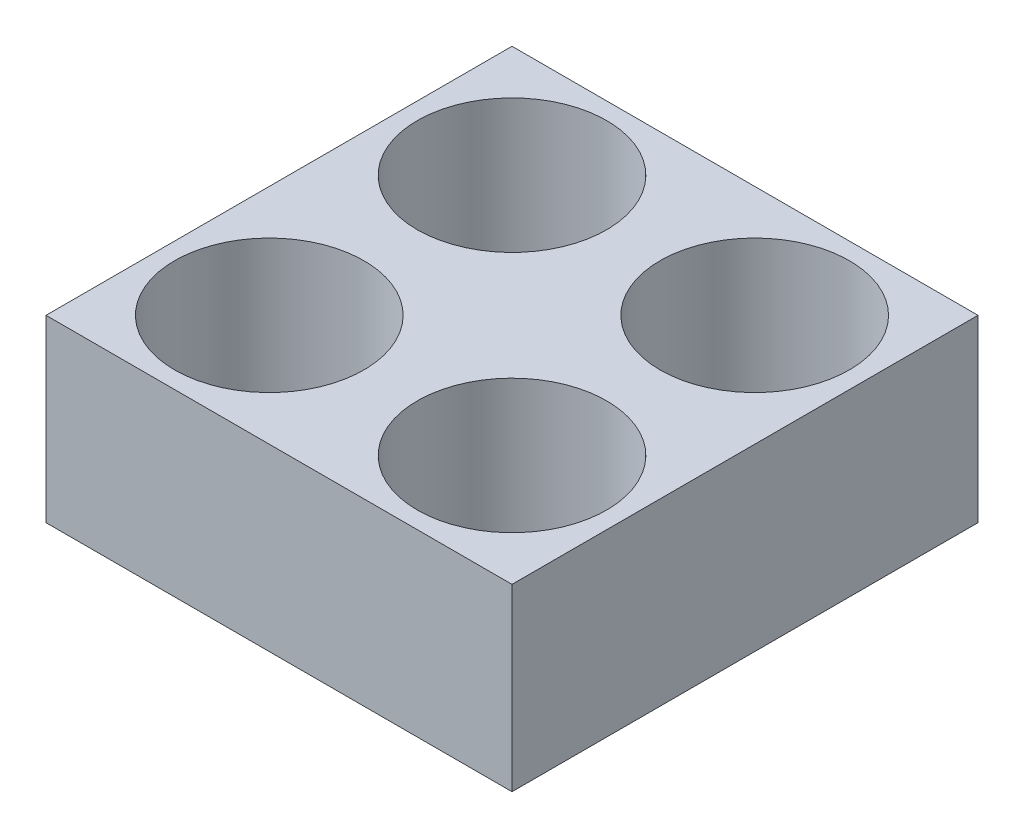
SolidWorks part; units mm, degrees
ref_plane "Front Plane" through (0, 0, 0) normal (0, 0, 1) x (1, 0, 0)
ref_plane "Top Plane" through (0, 0, 0) normal (0, 1, 0) x (1, 0, 0)
ref_plane "Right Plane" through (0, 0, 0) normal (1, 0, 0) x (0, 0, -1)
sketch "Sketch1" plane through (0, 0, 0) normal (0, 1, 0) x (1, 0, 0)
  line L0 (0, 50) -> (0, 0) construction
  line L1 (0, 0) -> (50, 0) construction
  line L2 (50, 0) -> (50, 50) construction
  line L3 (50, 50) -> (0, 50) construction
  line L4 (0, 25) -> (50, 25) construction
  line L5 (25, 50) -> (25, 0) construction
  line L7 (-23, -23) -> (73, -23)
  line L8 (-23, -23) -> (-23, 73)
  line L9 (-23, 73) -> (73, 73)
  line L10 (73, -23) -> (73, 73)
  line L11 (-23, -23) -> (73, 73) construction
  line L12 (-23, 73) -> (73, -23) construction
  circle A0 centre (0, 0) radius 19.5
  circle A1 centre (50, 0) radius 19.5
  circle A2 centre (50, 50) radius 19.5
  circle A3 centre (0, 50) radius 19.5
  point P13 (25, 25)
  dimension "D1" = 39
  dimension "D4" = 96
  dimension "D5" = 96
  dimension "D2" = 2
  dimension "D3" = 2
extrude "Boss-Extrude1" add sketch "Sketch1" along normal blind 35
sketch "Sketch2" plane through (0, 0, 0) normal (0, -1, 0) x (1, 0, 0)
  line L4 (73, -73) -> (73, 23)
  line L5 (73, 23) -> (-23, 23)
  line L6 (-23, 23) -> (-23, -73)
  line L7 (-23, -73) -> (73, -73)
  line L8 (73, -73) -> (73, 23)
  line L9 (73, 23) -> (-23, 23)
  line L10 (-23, 23) -> (-23, -73)
  line L11 (-23, -73) -> (73, -73)
  dimension "D1" = 0
extrude "Boss-Extrude2" add sketch "Sketch2" along normal blind 2
sketch "Sketch3" plane through (0, 0, 0) normal (0, 1, 0) x (1, 0, 0)
  line L0 (50, 30.5) -> (50, 69.5) construction
  line L1 (69.5, 50) -> (30.5, 50) construction
  line L2 (69.5, 0) -> (30.5, 0) construction
  line L3 (50, 19.5) -> (50, -19.5) construction
  line L4 (19.5, 0) -> (-19.5, 0) construction
  line L5 (0, -19.5) -> (0, 19.5) construction
  line L6 (0, 30.5) -> (0, 69.5) construction
  line L7 (19.5, 50) -> (-19.5, 50) construction
  circle A0 centre (50, 50) radius 19.5 construction
  circle A1 centre (57, 43) radius 3.6
  circle A2 centre (57, 57) radius 3.6
  circle A3 centre (43, 43) radius 3.6
  circle A4 centre (43, 57) radius 3.6
  circle A5 centre (50, 0) radius 19.5 construction
  circle A6 centre (0, 0) radius 19.5 construction
  circle A7 centre (0, 50) radius 19.5 construction
  circle A8 centre (57, 7) radius 3.6
  circle A9 centre (43, 7) radius 3.6
  circle A10 centre (43, -7) radius 3.6
  circle A11 centre (57, -7) radius 3.6
  circle A12 centre (7, 7) radius 3.6
  circle A13 centre (7, -7) radius 3.6
  circle A14 centre (-7, -7) radius 3.6
  circle A15 centre (-7, 7) radius 3.6
  circle A16 centre (7, 57) radius 3.6
  circle A17 centre (7, 43) radius 3.6
  circle A18 centre (-7, 43) radius 3.6
  circle A19 centre (-7, 57) radius 3.6
  dimension "D1" = 7
  dimension "D3" = 7.2
  dimension "D4" = 7.2
  dimension "D7" = 7.2
  dimension "D10" = 7.2
  dimension "D2" = 7
  dimension "D5" = 7
  dimension "D6" = 7
  dimension "D8" = 7
  dimension "D9" = 7
  dimension "D11" = 7
  dimension "D12" = 7
extrude "Cut-Extrude1" cut sketch "Sketch3" against normal through all
